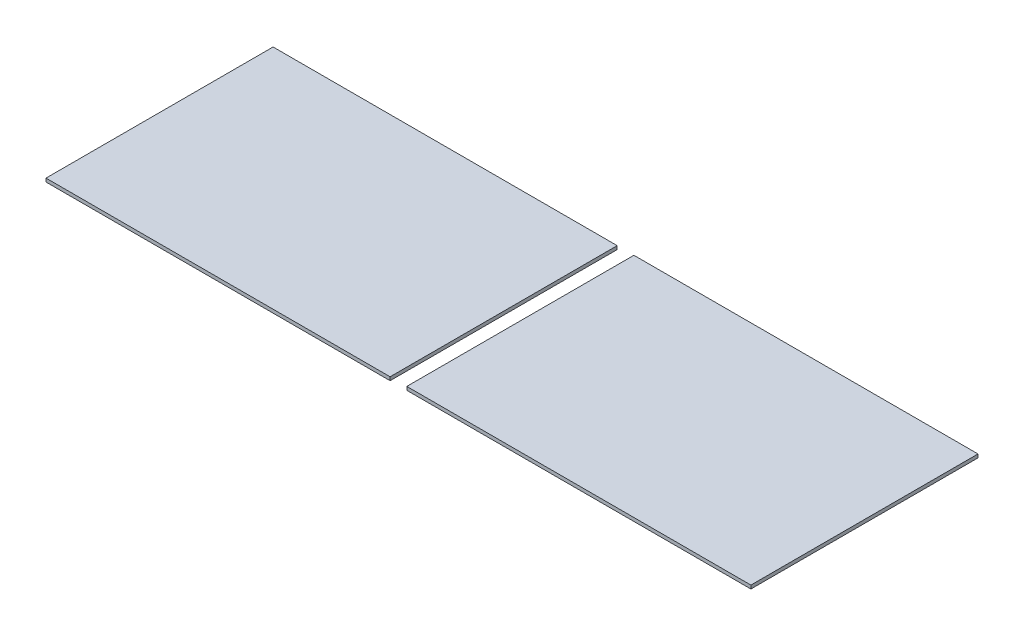
SolidWorks part; units mm, degrees
material "PE High Density"
ref_plane "Front Plane" through (0, 0, 0) normal (0, 0, 1) x (1, 0, 0)
ref_plane "Top Plane" through (0, 0, 0) normal (0, 1, 0) x (1, 0, 0)
ref_plane "Right Plane" through (0, 0, 0) normal (1, 0, 0) x (0, 0, -1)
sketch "Sketch1" plane through (0, 0, 0) normal (0, 1, 0) x (1, 0, 0)
  line L0 (12.1369, 165) -> (512.1369, 165)
  line L1 (12.1369, 165) -> (12.1369, -165)
  line L2 (512.1369, 165) -> (512.1369, -165)
  line L3 (12.1369, -165) -> (512.1369, -165)
  line L4 (12.1369, 165) -> (512.1369, -165) construction
  line L5 (512.1369, 165) -> (12.1369, -165) construction
  dimension "D1" = 500
  dimension "D2" = 330
extrude "Boss-Extrude1" add sketch "Sketch1" along normal blind 5
mirror "Mirror3" about plane through (0, 0, 0) normal (1, 0, 0) of bodies 101
